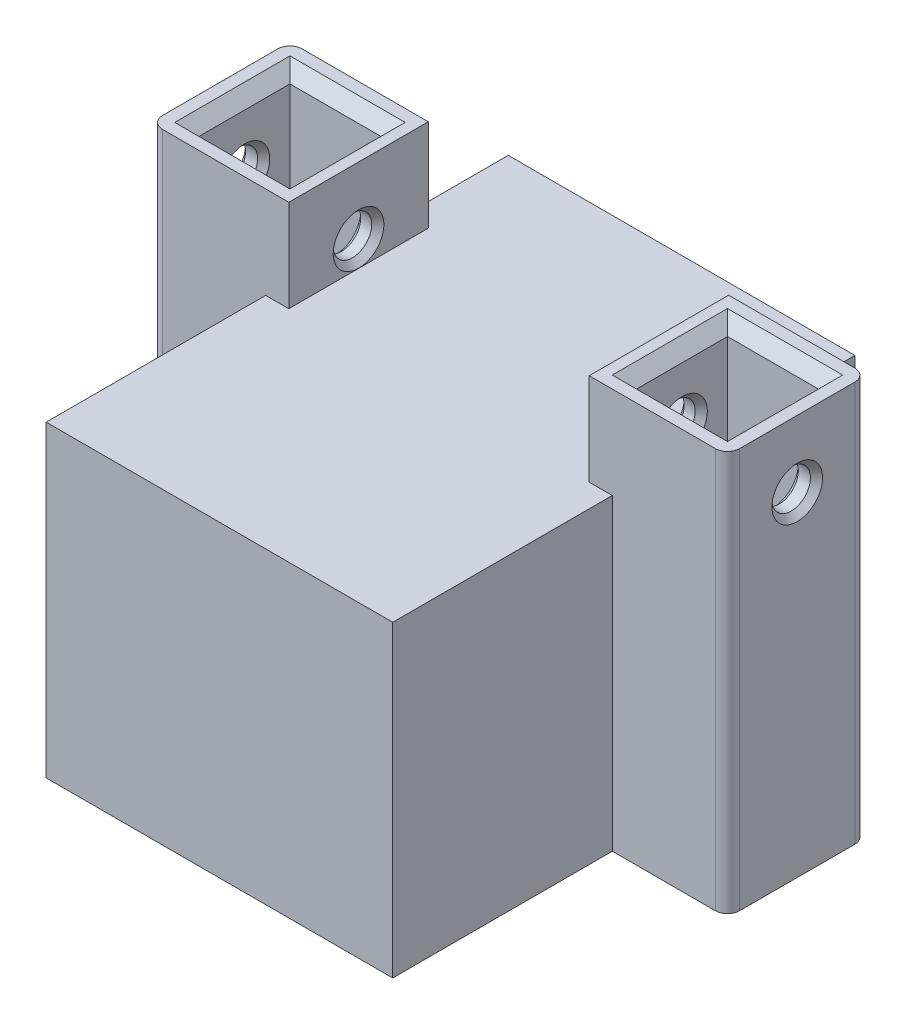
SolidWorks part; units mm, degrees
ref_plane "Front Plane" through (0, 0, 0) normal (0, 0, 1) x (1, 0, 0)
ref_plane "Top Plane" through (0, 0, 0) normal (0, 1, 0) x (1, 0, 0)
ref_plane "Right Plane" through (0, 0, 0) normal (1, 0, 0) x (0, 0, -1)
sketch "Sketch3" plane through (0, 0, 0) normal (0, 1, 0) x (-1, 0, 0)
  line L1 (0, 0) -> (57.15, 0)
  line L2 (0, 0) -> (0, 76.2)
  line L3 (0, 76.2) -> (57.15, 76.2)
  line L4 (57.15, 0) -> (57.15, 76.2)
  dimension "D1" = 76.2
  dimension "D2" = 57.15
extrude "Boss-Extrude2" add sketch "Sketch3" against normal blind 50.8
sketch "Sketch4" plane through (0, -50.8, 0) normal (0, -1, 0) x (1, 0, 0)
  line L1 (-3.81, 72.39) -> (-53.34, 72.39)
  line L2 (-3.81, 72.39) -> (-3.81, 3.81)
  line L3 (-3.81, 3.81) -> (-53.34, 3.81)
  line L4 (-53.34, 72.39) -> (-53.34, 3.81)
  line L8 (-57.15, 76.2) -> (0, 76.2) construction
  line L9 (0, 0) -> (-57.15, 0) construction
  line L10 (0, 76.2) -> (0, 0) construction
  line L11 (-57.15, 0) -> (-57.15, 76.2) construction
  dimension "D1" = 3.81
  dimension "D2" = 3.81
  dimension "D3" = 3.81
  dimension "D4" = 3.81
extrude "Cut-Extrude2" cut sketch "Sketch4" against normal blind 44.45
sketch "Sketch5" plane through (-57.15, 0, 0) normal (1, 0, 0) x (0, 0, -1)
  line L1 (-14.478, -46.99) -> (-5.08, -46.99)
  line L2 (-14.478, -46.99) -> (-14.478, -35.56)
  line L3 (-14.478, -35.56) -> (-5.08, -35.56)
  line L4 (-5.08, -46.99) -> (-5.08, -35.56)
  line L6 (0, -50.8) -> (0, 0) construction
  line L7 (0, -50.8) -> (-76.2, -50.8) construction
  dimension "D1" = 5.08
  dimension "D2" = 3.81
  dimension "D3" = 11.43
  dimension "D4" = 9.398
extrude "Cut-Extrude3" cut sketch "Sketch5" along normal up to next
sketch "Sketch6" plane through (-57.15, 0, 0) normal (-1, 0, 0) x (0, 0, 1)
  line L0 (46.54, 0) -> (46.54, 36.83)
  line L1 (46.54, 36.83) -> (0, 36.83)
  line L2 (0, 36.83) -> (0, 34.29)
  line L3 (0, 34.29) -> (44, 34.29)
  line L4 (44, 34.29) -> (44, 0)
  line L5 (0, 0) -> (76.2, 0) construction
  line L6 (44, 0) -> (46.54, 0)
  line L7 (0, -50.8) -> (0, 0) construction
  dimension "D1" = 44
  dimension "D2" = 34.29
  dimension "D3" = 2.54
  dimension "D4" = 2.54
extrude "Motor Mounting Shape" add sketch "Sketch6" against normal up to surface (57.15 mm away) up to face at (0, -25.4, 38.1)
sketch "Sketch8" plane through (0, 36.83, 0) normal (0, 1, 0) x (1, 0, 0)
  line L0 (-44.075, -38.77) -> (-13.075, -7.77) construction
  line L1 (-13.075, -38.77) -> (-44.075, -7.77) construction
  line L2 (-44.075, -38.77) -> (-44.075, -7.77) construction
  line L3 (-44.075, -7.77) -> (-13.075, -7.77) construction
  line L4 (-28.575, -46.54) -> (-28.575, 0) construction
  line L5 (0, -46.54) -> (-57.15, -46.54) construction
  line L6 (0, 0) -> (-57.15, 0) construction
  line L7 (-37.465, 0) -> (-19.685, 0)
  line L8 (-19.685, 0) -> (-19.685, -23.27)
  line L9 (-37.465, -23.27) -> (-37.465, 0)
  circle A1 centre (-44.075, -7.77) radius 1.6
  circle A2 centre (-13.075, -7.77) radius 1.6
  circle A3 centre (-13.075, -38.77) radius 1.6
  circle A4 centre (-44.075, -38.77) radius 1.6
  arc A6 (-37.465, -23.27) -> (-19.685, -23.27) centre (-28.575, -23.27) ccw
  point P10 (-28.575, -23.27)
  dimension "D2" = 3.2
  dimension "D3" = 8.89
  dimension "D1" = 31
extrude "Motor-Mounting-Holes" cut sketch "Sketch8" against normal up to next
sketch "Sketch7" plane through (0, 0, 0) normal (0, 1, 0) x (1, 0, 0)
  line L0 (-46.355, -76.2) -> (-46.355, -46.54)
  line L1 (-57.15, -76.2) -> (0, -76.2) construction
  line L2 (-46.355, -46.54) -> (-38.735, -46.54)
  line L3 (-38.735, -46.54) -> (-38.735, -76.2)
  line L4 (-38.735, -76.2) -> (-46.355, -76.2)
  line L5 (-18.415, -76.2) -> (-10.795, -76.2)
  line L6 (-10.795, -76.2) -> (-10.795, -46.54)
  line L7 (-10.795, -46.54) -> (-18.415, -46.54)
  line L8 (-18.415, -46.54) -> (-18.415, -76.2)
  line L9 (-46.355, -76.2) -> (-57.15, -76.2) construction
  line L10 (-38.735, -76.2) -> (-18.415, -76.2) construction
  line L11 (-10.795, -76.2) -> (0, -76.2) construction
  line L12 (0, -46.54) -> (-57.15, -46.54) construction
  dimension "D1" = 7.62
  dimension "D2" = 20.32
extrude "Tray Support Mounting Shape" add sketch "Sketch7" along normal blind 44.45
sketch "Sketch9" plane through (0, -50.8, 0) normal (0, -1, 0) x (1, 0, 0)
  line L0 (0, 40) -> (-3.81, 40)
  line L1 (0, 17) -> (19, 17)
  line L2 (0, 21) -> (0, 36)
  line L3 (0, 40) -> (19, 40)
  line L5 (19, 40) -> (19, 17)
  line L6 (0, 36) -> (15, 36)
  line L7 (15, 36) -> (15, 21)
  line L8 (15, 21) -> (0, 21)
  line L9 (-3.81, 3.81) -> (-3.81, 72.39) construction
  line L10 (-3.81, 40) -> (-3.81, 17)
  line L11 (-28.575, 76.2) -> (-28.575, 0) construction
  line L12 (-3.81, 17) -> (0, 17)
  line L13 (0, 36) -> (0, 21)
  line L14 (0, 0) -> (-57.15, 0) construction
  line L15 (-57.15, 76.2) -> (0, 76.2) construction
  line L16 (-72.15, 36) -> (-72.15, 21)
  line L17 (-72.15, 21) -> (-57.15, 21)
  line L18 (-57.15, 21) -> (-57.15, 36)
  line L19 (-57.15, 36) -> (-72.15, 36)
  line L20 (-53.34, 17) -> (-57.15, 17)
  line L21 (-53.34, 40) -> (-53.34, 17)
  line L22 (-57.15, 40) -> (-53.34, 40)
  line L23 (-57.15, 40) -> (-76.15, 40)
  line L24 (-76.15, 40) -> (-76.15, 17)
  line L25 (-57.15, 17) -> (-76.15, 17)
  dimension "D1" = 4
  dimension "D2" = 4
  dimension "D3" = 4
  dimension "D4" = 15
  dimension "D5" = 3.81
  dimension "D6" = 3.81
  dimension "D7" = 17
extrude "Boss-Extrude3" add sketch "Sketch9" against normal blind 66 contours L1 L5 L3 L0 L10 L12 | L13 L8 L7 L6 | L20 L25 L24 L23 L22 L21 | L16 L17 L18 L19
sketch "Sketch10" plane through (-76.15, 0, 0) normal (-1, 0, 0) x (0, 0, 1)
  line L1 (17, 15.2) -> (40, 15.2) construction
  line L2 (40, -50.8) -> (17, -50.8) construction
  circle A0 centre (28.5, 4.2) radius 3.175
  point P2 (28.5, 15.2)
  dimension "D1" = 6.35
  dimension "D2" = 55
extrude "Cut-Extrude4" cut sketch "Sketch10" against normal through all
chamfer "Chamfer1" distance 2 angle 45 8 edges at (-57.15, 15.2, 28.5) (-64.65, 15.2, 21) (-72.15, 15.2, 28.5) (-64.65, 15.2, 36) (7.5, 15.2, 21) (0, 15.2, 28.5) (15, 15.2, 28.5) (7.5, 15.2, 36)
fillet "Fillet1" radius 2 4 edges at (-76.15, -17.8, 40) (-76.15, -17.8, 17) (19, -17.8, 40) (19, -17.8, 17)
chamfer "Chamfer2" distance 1 angle 45 8 edges at (19, 4.2, 31.675) (15, 4.2, 31.675) (-3.81, 4.2, 31.675) (0, 4.2, 25.325) (-53.34, 4.2, 31.675) (-57.15, 4.2, 31.675) (-72.15, 4.2, 31.675) (-76.15, 4.2, 31.675)
sketch "Sketch11" plane through (0, 0, 0) normal (1, 0, 0) x (0, 0, -1)
  line L0 (-44, 0) -> (-44, 34.29)
  line L1 (-44, 34.29) -> (0, 34.29)
  line L2 (0, 34.29) -> (0, 51.5993)
  line L3 (0, 51.5993) -> (-81.1962, 51.5993)
  line L4 (-81.1962, 51.5993) -> (-81.1962, 0)
  line L5 (-81.1962, 0) -> (-44, 0)
extrude "Cut-Extrude5" cut sketch "Sketch11" against normal through all
